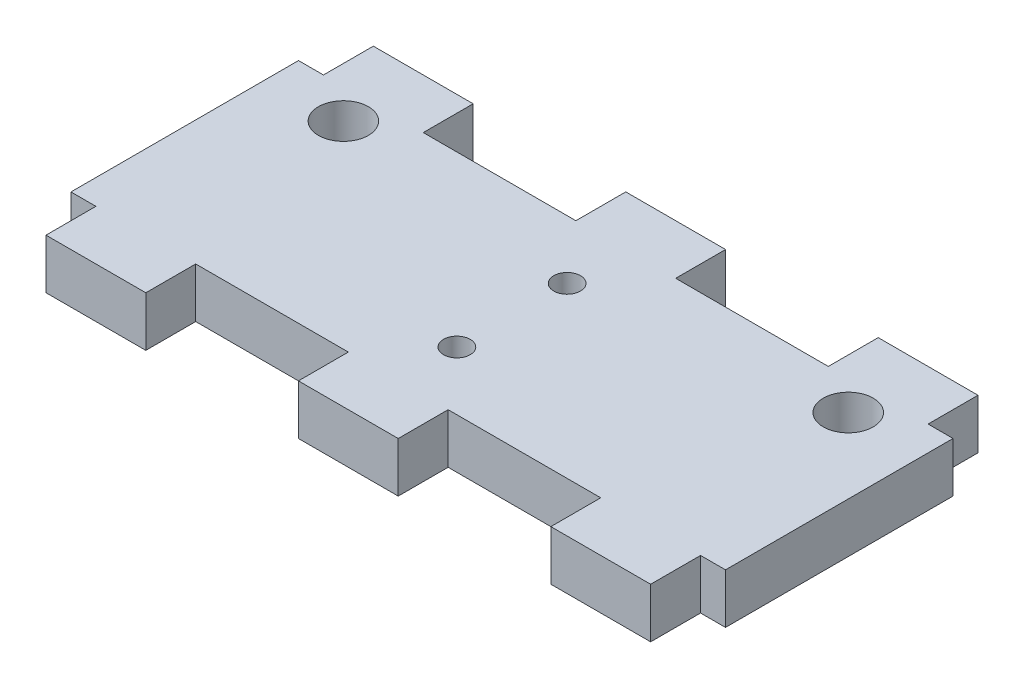
SolidWorks part; units mm, degrees
material "Acrylic (Medium-high impact)"
ref_plane "Front Plane" through (0, 0, 0) normal (0, 0, 1) x (1, 0, 0)
ref_plane "Top Plane" through (0, 0, 0) normal (0, 1, 0) x (1, 0, 0)
ref_plane "Right Plane" through (0, 0, 0) normal (1, 0, 0) x (0, 0, -1)
sketch "Sketch1" plane through (0, 0, 0) normal (0, 1, 0) x (1, 0, 0)
  line L0 (-41.6458, 14.478) -> (-38.4708, 14.478)
  line L1 (41.6458, -14.478) -> (-41.6458, -14.478) construction
  line L2 (41.6458, -14.478) -> (41.6458, 14.478)
  line L3 (41.6458, 14.478) -> (-41.6458, 14.478) construction
  line L4 (-41.6458, -14.478) -> (-41.6458, 14.478)
  line L5 (41.6458, -14.478) -> (-41.6458, 14.478) construction
  line L6 (41.6458, 14.478) -> (-41.6458, -14.478) construction
  line L7 (-38.4708, 14.478) -> (-38.4708, 20.828)
  line L8 (-38.4708, 20.828) -> (-25.7708, 20.828)
  line L9 (-25.7708, 20.828) -> (-25.7708, 14.478)
  line L10 (-25.7708, 14.478) -> (-6.35, 14.478)
  line L11 (-6.35, 14.478) -> (-6.35, 20.828)
  line L12 (-6.35, 20.828) -> (6.35, 20.828)
  line L13 (6.35, 20.828) -> (6.35, 14.478)
  line L14 (6.35, 14.478) -> (25.7708, 14.478)
  line L15 (25.7708, 14.478) -> (25.7708, 20.828)
  line L16 (25.7708, 20.828) -> (38.4708, 20.828)
  line L17 (38.4708, 20.828) -> (38.4708, 14.478)
  line L18 (38.4708, 14.478) -> (41.6458, 14.478)
  line L19 (-41.6458, -14.478) -> (-38.4708, -14.478)
  line L20 (-38.4708, -14.478) -> (-38.4708, -20.828)
  line L21 (-38.4708, -20.828) -> (-25.7708, -20.828)
  line L22 (-25.7708, -20.828) -> (-25.7708, -14.478)
  line L23 (-25.7708, -14.478) -> (-6.35, -14.478)
  line L24 (-6.35, -14.478) -> (-6.35, -20.828)
  line L25 (-6.35, -20.828) -> (6.35, -20.828)
  line L26 (6.35, -20.828) -> (6.35, -14.478)
  line L27 (6.35, -14.478) -> (25.7708, -14.478)
  line L28 (25.7708, -14.478) -> (25.7708, -20.828)
  line L29 (25.7708, -20.828) -> (38.4708, -20.828)
  line L30 (38.4708, -20.828) -> (38.4708, -14.478)
  line L31 (38.4708, -14.478) -> (41.6458, -14.478)
  line L32 (-41.6458, 1.778) -> (41.6458, 1.778) construction
  line L33 (-41.6458, -1.778) -> (41.6458, -1.778) construction
  line L34 (0, 20.828) -> (0, 1.778) construction
  line L35 (-32.1208, -20.828) -> (-32.1208, -1.778) construction
  line L36 (-32.1208, -7.0155) -> (32.1208, -7.0155) construction
  line L37 (32.1208, -7.0155) -> (32.1208, -20.828) construction
  line L38 (-32.1208, 20.828) -> (-32.1208, 10.668) construction
  line L39 (-32.1208, 10.668) -> (32.1208, 10.668) construction
  line L40 (32.1208, 10.668) -> (32.1208, 20.828) construction
  circle A0 centre (32.1208, 10.668) radius 3.175
  circle A1 centre (-32.1208, -7.0155) radius 1.7005 construction
  circle A2 centre (0, 7.0155) radius 1.7005
  circle A3 centre (-32.1208, 10.668) radius 3.175
  circle A4 centre (32.1208, -7.0155) radius 1.7005 construction
  circle A5 centre (0, -7.0155) radius 1.7005
  point P0 (0, 0)
  dimension "D11" = 10.16
  dimension "D8" = 3.4011
  dimension "D12" = 6.35
  dimension "D1" = 12.7
  dimension "D2" = 6.35
  dimension "D3" = 3.175
  dimension "D4" = 12.7
  dimension "D5" = 12.7
  dimension "D6" = 28.956
  dimension "D7" = 83.2917
  dimension "D9" = 7.4625
  dimension "D10" = 5.2375
extrude "Boss-Extrude1" add sketch "Sketch1" along normal blind 6.35
